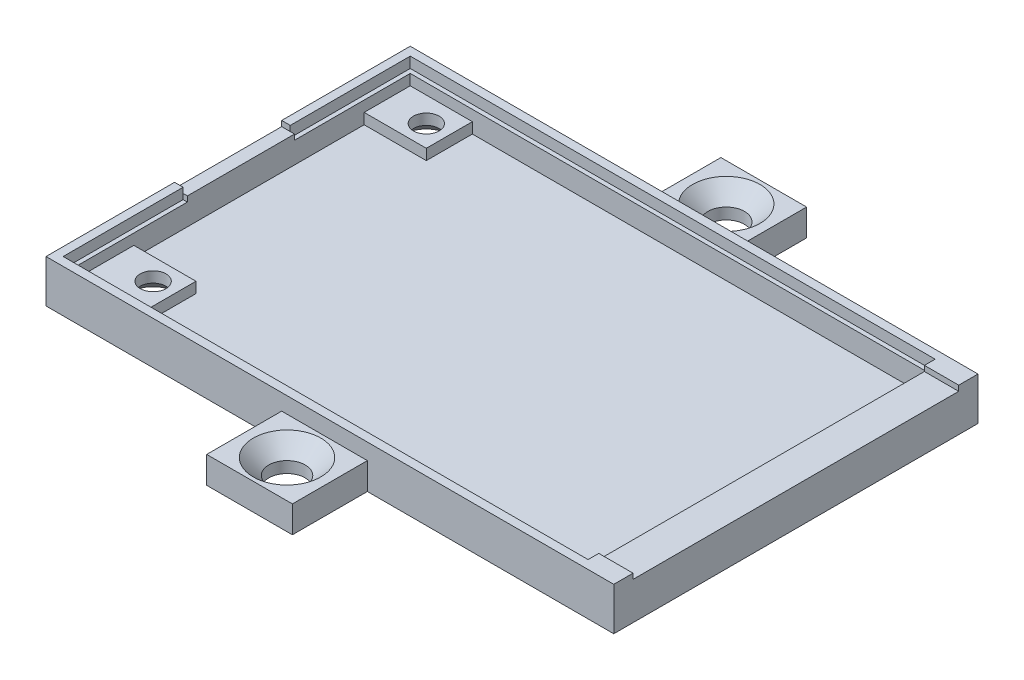
SolidWorks part; units mm, degrees
ref_plane "Front Plane" through (0, 0, 0) normal (0, 0, 1) x (1, 0, 0)
ref_plane "Top Plane" through (0, 0, 0) normal (0, 1, 0) x (1, 0, 0)
ref_plane "Right Plane" through (0, 0, 0) normal (1, 0, 0) x (0, 0, -1)
sketch "Sketch1" plane through (0, 0, 0) normal (0, 1, 0) x (1, 0, 0)
  line L1 (0, 0) -> (53, 0)
  line L2 (0, 0) -> (0, 34)
  line L3 (0, 34) -> (53, 34)
  line L4 (53, 0) -> (53, 34)
  dimension "D1" = 53
  dimension "D2" = 34
extrude "Boss-Extrude1" add sketch "Sketch1" along normal blind 4
sketch "Sketch2" plane through (0, 0, 0) normal (0, 1, 0) x (1, 0, 0)
  line L0 (0, 0) -> (53, 0) construction
  line L1 (22, 0) -> (30, 0)
  line L2 (22, 0) -> (22, -7)
  line L3 (22, -7) -> (30, -7)
  line L4 (30, 0) -> (30, -7)
  line L5 (26, 0) -> (26, -7) construction
  line L7 (53, 0) -> (53, 34) construction
  line L8 (26, -3.5) -> (26, 37.5) construction
  line L9 (53, 34) -> (0, 34) construction
  line L10 (30, 41) -> (22, 41)
  line L11 (30, 41) -> (30, 34)
  line L12 (30, 34) -> (22, 34)
  line L13 (22, 41) -> (22, 34)
  line L14 (30, 41) -> (22, 34) construction
  line L15 (30, 34) -> (22, 41) construction
  dimension "D1" = 7
  dimension "D2" = 8
  dimension "D3" = 27
  dimension "D4" = 41
  dimension "D5" = 8
extrude "Boss-Extrude2" add sketch "Sketch2" along normal blind 2.5
sketch "Sketch3" plane through (0, 4, 0) normal (0, 1, 0) x (1, 0, 0)
  line L0 (53, 34) -> (0, 34) construction
  line L6 (1.2, 32.8) -> (49.8, 32.8)
  line L7 (1.2, 32.8) -> (1.2, 1.2)
  line L10 (1.2, 1.2) -> (49.8, 1.2)
  line L11 (49.8, 32.8) -> (49.8, 1.2)
  line L12 (0, 34) -> (0, 0) construction
  line L13 (0, 0) -> (53, 0) construction
  line L14 (53, 0) -> (53, 34) construction
  dimension "D1" = 1.2
  dimension "D2" = 1.2
  dimension "D3" = 1.2
  dimension "D4" = 3.2
extrude "Cut-Extrude1" cut sketch "Sketch3" against normal blind 3
sketch "Sketch4" plane through (0, 1, 0) normal (0, 1, 0) x (1, 0, 0)
  line L1 (1.2, 32.8) -> (7, 32.8)
  line L2 (1.2, 32.8) -> (1.2, 28.5)
  line L3 (1.2, 28.5) -> (7, 28.5)
  line L4 (7, 32.8) -> (7, 28.5)
  line L5 (1.2, 1.2) -> (7, 1.2)
  line L6 (1.2, 1.2) -> (1.2, 7)
  line L7 (1.2, 7) -> (7, 7)
  line L8 (7, 1.2) -> (7, 7)
  dimension "D1" = 5.8
  dimension "D2" = 4.3
  dimension "D3" = 5.8
  dimension "D4" = 5.8
extrude "Boss-Extrude3" add sketch "Sketch4" along normal blind 1
sketch "Sketch5" plane through (0, 4, 0) normal (0, 1, 0) x (1, 0, 0)
  line L0 (49.8, 32.8) -> (1.2, 32.8)
  line L1 (1.2, 32.8) -> (1.2, 22)
  line L2 (1.2, 32.8) -> (1.2, 1.2) construction
  line L3 (49.8, 1.2) -> (1.2, 1.2)
  line L4 (1.2, 1.2) -> (1.2, 12)
  line L5 (1.2, 28.5) -> (1.2, 7) construction
  line L6 (49.8, 33.2) -> (0.8, 33.2)
  line L7 (0.8, 33.2) -> (0.8, 22)
  line L8 (49.8, 0.8) -> (0.8, 0.8)
  line L9 (0.8, 0.8) -> (0.8, 12)
  line L10 (0.8, 22) -> (1.2, 22)
  line L11 (49.8, 32.8) -> (49.8, 33.2)
  line L12 (49.8, 1.2) -> (49.8, 0.8)
  line L13 (1.2, 12) -> (0.8, 12)
  dimension "D1" = 10.8
  dimension "D2" = 10.8
  dimension "D3" = 0.4
  dimension "D4" = 0.4
extrude "Cut-Extrude2" cut sketch "Sketch5" against normal blind 1
sketch "Sketch6" plane through (0, 4, 0) normal (0, 1, 0) x (1, 0, 0)
  line L0 (0, 34) -> (0, 0) construction
  line L1 (1.2, 22) -> (0, 22)
  line L2 (1.2, 22) -> (1.2, 12)
  line L3 (1.2, 12) -> (0, 12)
  line L4 (0, 22) -> (0, 12)
  line L5 (49.8, 0.8) -> (49.8, 33.2) construction
  line L6 (49.8, 32.2) -> (53, 32.2)
  line L7 (49.8, 32.2) -> (49.8, 1.8)
  line L8 (49.8, 1.8) -> (53, 1.8)
  line L9 (53, 32.2) -> (53, 1.8)
  line L10 (53, 0) -> (53, 34) construction
  line L11 (53, 34) -> (0, 34) construction
  dimension "D1" = 10
  dimension "D2" = 1.8
  dimension "D3" = 30.4
extrude "Cut-Extrude3" cut sketch "Sketch6" against normal blind 0.5
sketch "Sketch7" plane through (0, 2.5, 0) normal (0, 1, 0) x (1, 0, 0)
  line L0 (22, 34) -> (30, 41) construction
  line L1 (30, -7) -> (22, 0) construction
  point P8 (26, 37.5)
  point P9 (26, -3.5)
hole_wizard "CSK for M3 Countersunk Flat Head Screw1" positions "3DSketch1" profile "Sketch8" countersink size "M3" standard "DIN" end condition through all
sketch3d "3DSketch1"
  point P0 (26, 2.5, -37.5)
  point P3 (26, 2.5, 3.5)
sketch "Sketch8" plane through (26, 2.5, -37.5) normal (1, 0, 0) x (0, 0, 1)
  line L0 (0, 0) -> (0, 2.5)
  line L1 (0, 2.5) -> (1.7, 2.5)
  line L2 (1.7, 2.5) -> (1.7, 1.45)
  line L3 (1.7, 1.45) -> (3.15, 0)
  line L5 (3.15, 0) -> (0, 0)
  line L6 (-1.7, 1.45) -> (-3.15, 0) construction
  line L11 (0, -6.35) -> (0, 107.95) construction
  dimension "Thru Hole Dia." = 3.4
  dimension "Thru Hole Depth" = 2.5
  dimension "Near C'Sink Dia." = 6.3
  dimension "Near C'Sink Angle" = 90
sketch "Sketch9" plane through (0, 0, 0) normal (0, -1, 0) x (1, 0, 0)
  line L0 (5, -30.5) -> (5, -5) construction
  line L1 (0, -34) -> (0, 0) construction
  line L3 (0, 0) -> (22, 0) construction
  dimension "D1" = 5
  dimension "D2" = 5
  dimension "D3" = 25.5
hole_wizard "CSK for M2 Countersunk Flat Head Screw1" positions "3DSketch2" profile "Sketch10" countersink size "M2" standard "DIN" end condition through all
sketch3d "3DSketch2"
  point P0 (5, 0, -5)
  point P3 (5, 0, -30.5)
sketch "Sketch10" plane through (5, 0, -5) normal (1, 0, 0) x (0, 0, -1)
  line L0 (0, 0) -> (0, 4)
  line L1 (0, 4) -> (1.2, 4)
  line L2 (1.2, 4) -> (1.2, 1)
  line L3 (1.2, 1) -> (2.2, 0)
  line L5 (2.2, 0) -> (0, 0)
  line L6 (-1.2, 1) -> (-2.2, 0) construction
  line L11 (0, -6.35) -> (0, 107.95) construction
  dimension "Thru Hole Dia." = 2.4
  dimension "Thru Hole Depth" = 4
  dimension "Near C'Sink Dia." = 4.4
  dimension "Near C'Sink Angle" = 90
